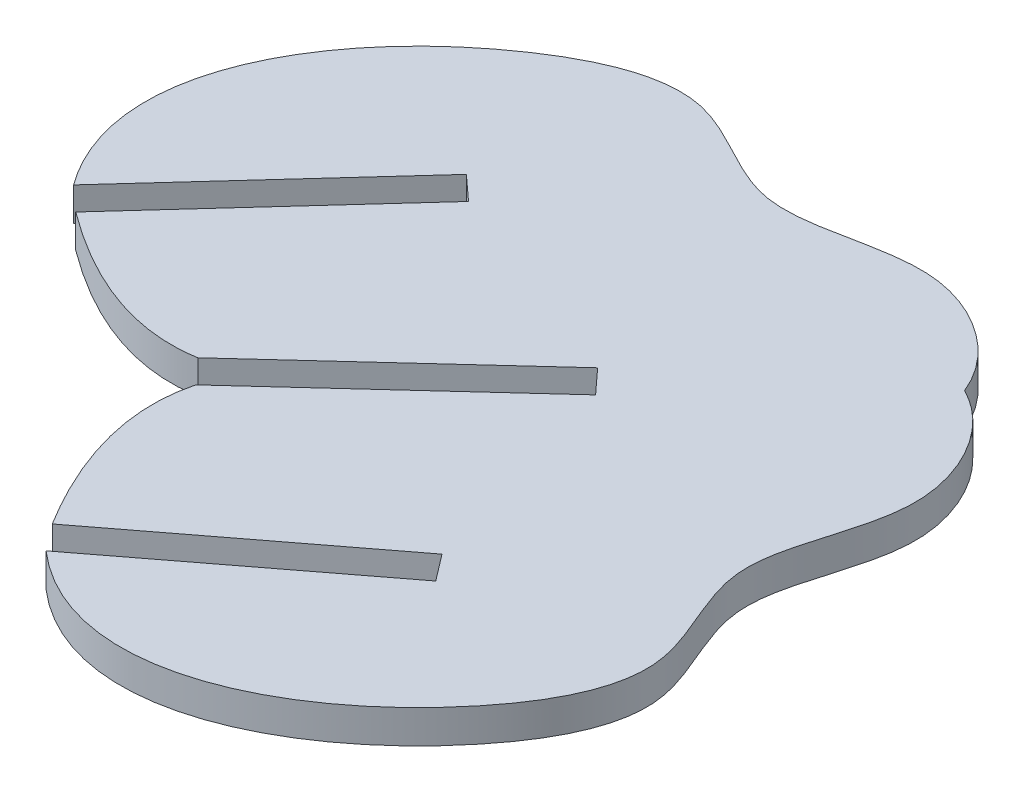
SolidWorks part; units mm, degrees
ref_plane "Спереди" through (0, 0, 0) normal (0, 0, 1) x (1, 0, 0)
ref_plane "Сверху" through (0, 0, 0) normal (0, 1, 0) x (1, 0, 0)
ref_plane "Справа" through (0, 0, 0) normal (1, 0, 0) x (0, 0, -1)
sketch "Эскиз1" plane through (0, 0, 0) normal (0, 1, 0) x (1, 0, 0)
  line L0 (67.558, 140.4457) -> (334.2247, 140.4457) construction
  line L7 (6.0599, 118.3927) -> (28.594, 143.1259)
  line L8 (28.594, 143.1259) -> (31.5508, 140.432)
  line L9 (31.5508, 140.432) -> (9.0167, 115.6988)
  line L10 (31.5508, 107.8593) -> (56.649, 130.8667)
  line L11 (56.649, 130.8667) -> (59.352, 127.9181)
  line L13 (69.1308, 98.9052) -> (66.7036, 102.0846)
  line L14 (42.5357, 78.602) -> (69.1308, 98.9052)
  line L15 (66.7036, 102.0846) -> (40.1085, 81.7815)
  line L16 (34.2537, 104.9107) -> (59.352, 127.9181)
  spline S2 degree 3 poles (6.0599, 118.3927) (-4.2662, 132.6223) (8.6009, 155.8726) (35.0629, 167.647) (49.8309, 154.9547) (66.9305, 164.3035) (79.0123, 155.845) (81.0994, 150.567) knots 0 0 0 0 0.411773 0.56077 0.685497 0.854203 1 1 1 1
  spline S3 degree 2 poles (9.0167, 115.6988) (21.8317, 106.1942) (31.5508, 107.8593) knots 0 0 0 1 1 1
  spline S8 degree 3 poles (42.5357, 78.602) (55.8157, 67.0803) (80.0948, 77.8815) (94.1207, 103.2222) (82.7576, 119.0357) (93.5547, 135.2597) (86.1764, 148.0298) (81.0994, 150.567) knots 0 0 0 0 0.411773 0.56077 0.685497 0.854203 1 1 1 1
  spline S11 degree 2 poles (40.1085, 81.7815) (31.7517, 95.3727) (34.2537, 104.9107) knots 0 0 0 1 1 1
extrude "Бобышка-Вытянуть1" add sketch "Эскиз1" along normal blind 4
